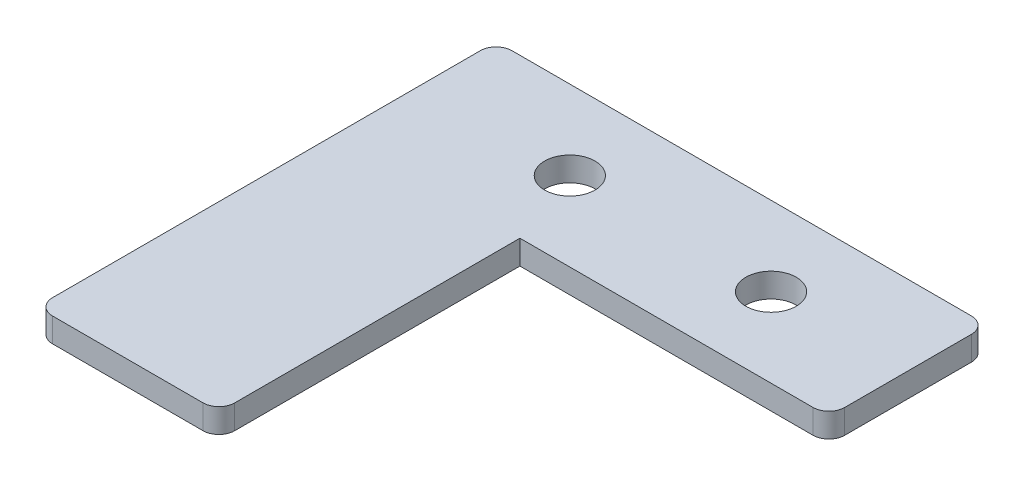
SolidWorks part; units mm, degrees
ref_plane "Front Plane" through (0, 0, 0) normal (0, 0, 1) x (1, 0, 0)
ref_plane "Top Plane" through (0, 0, 0) normal (0, 1, 0) x (1, 0, 0)
ref_plane "Right Plane" through (0, 0, 0) normal (1, 0, 0) x (0, 0, -1)
sketch "Sketch1" plane through (0, 0, 0) normal (0, 1, 0) x (1, 0, 0)
  line L0 (0, 0) -> (12.7, 0) construction
  line L1 (-3.65, 5) -> (16.35, 5)
  line L2 (-3.65, 5) -> (-3.65, -5)
  line L3 (-3.65, -5) -> (16.35, -5)
  line L4 (16.35, 5) -> (16.35, -5)
  line L5 (1.85, -5) -> (1.85, -24)
  line L6 (16.35, 5) -> (21.35, 5)
  line L7 (16.35, 5) -> (16.35, -5)
  line L8 (16.35, -5) -> (21.35, -5)
  line L9 (21.35, 5) -> (21.35, -5)
  line L10 (-3.65, -5) -> (21.35, -5)
  line L11 (-3.65, -5) -> (-3.65, -24)
  line L12 (-3.65, -24) -> (21.35, -24)
  line L13 (21.35, -5) -> (21.35, -24)
  line L14 (-3.65, 5) -> (-9.65, 5)
  line L15 (-3.65, 5) -> (-3.65, -24)
  line L16 (-3.65, -24) -> (-9.65, -24)
  line L17 (-9.65, 5) -> (-9.65, -24)
  circle A0 centre (0, 0) radius 1.59
  circle A1 centre (12.7, 0) radius 1.59
  point P6 (16.35, 0)
  point P11 (6.35, 5)
  point P12 (6.35, 0)
  dimension "D1" = 3.18
  dimension "D2" = 20
  dimension "D3" = 12.7
  dimension "D4" = 10
  dimension "D5" = 5
  dimension "D6" = 19
  dimension "D7" = 6
  dimension "D8" = 5.5
extrude "Boss-Extrude1" add sketch "Sketch1" along normal blind 1.524
fillet "Fillet1" radius 1 5 edges at (-9.65, 0.762, -5) (21.35, 0.762, -5) (21.35, 0.762, 5) (1.85, 0.762, 24) (-9.65, 0.762, 24)
